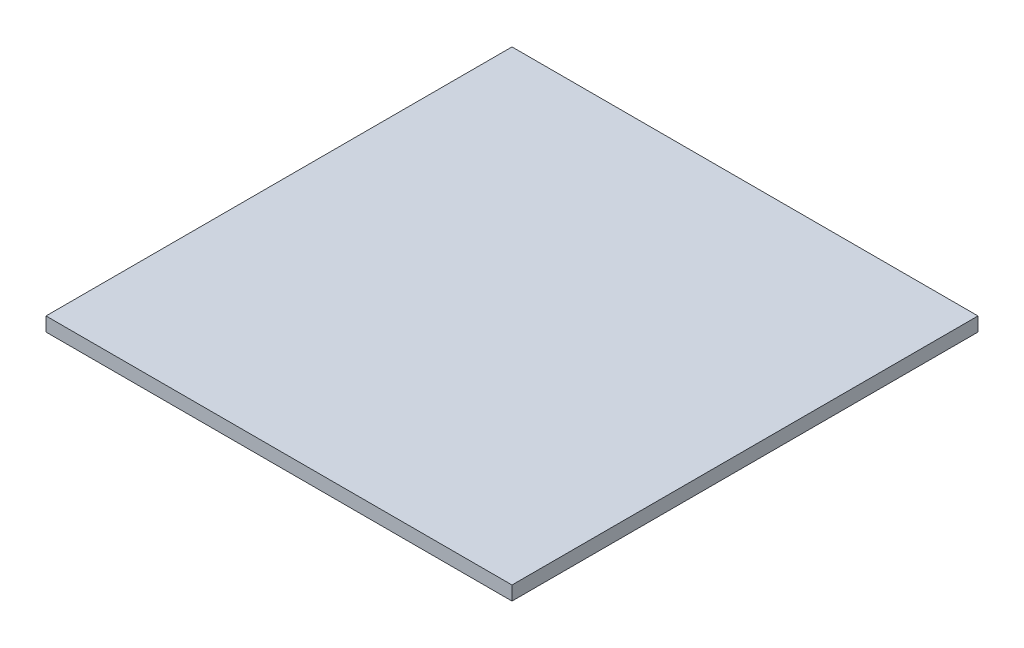
SolidWorks part; units mm, degrees
ref_plane "Front Plane" through (0, 0, 0) normal (0, 0, 1) x (1, 0, 0)
ref_plane "Top Plane" through (0, 0, 0) normal (0, 1, 0) x (1, 0, 0)
ref_plane "Right Plane" through (0, 0, 0) normal (1, 0, 0) x (0, 0, -1)
sketch "Sketch3" plane through (0, 0, 0) normal (0, 1, 0) x (1, 0, 0)
  line L1 (-50, 50) -> (50, 50)
  line L2 (-50, 50) -> (-50, -50)
  line L3 (-50, -50) -> (50, -50)
  line L4 (50, 50) -> (50, -50)
  line L5 (-50, 50) -> (50, -50) construction
  line L6 (-50, -50) -> (50, 50) construction
  point P0 (0, 0)
  dimension "D1" = 100
  dimension "D2" = 100
extrude "Boss-Extrude3" add sketch "Sketch3" along normal blind 3
